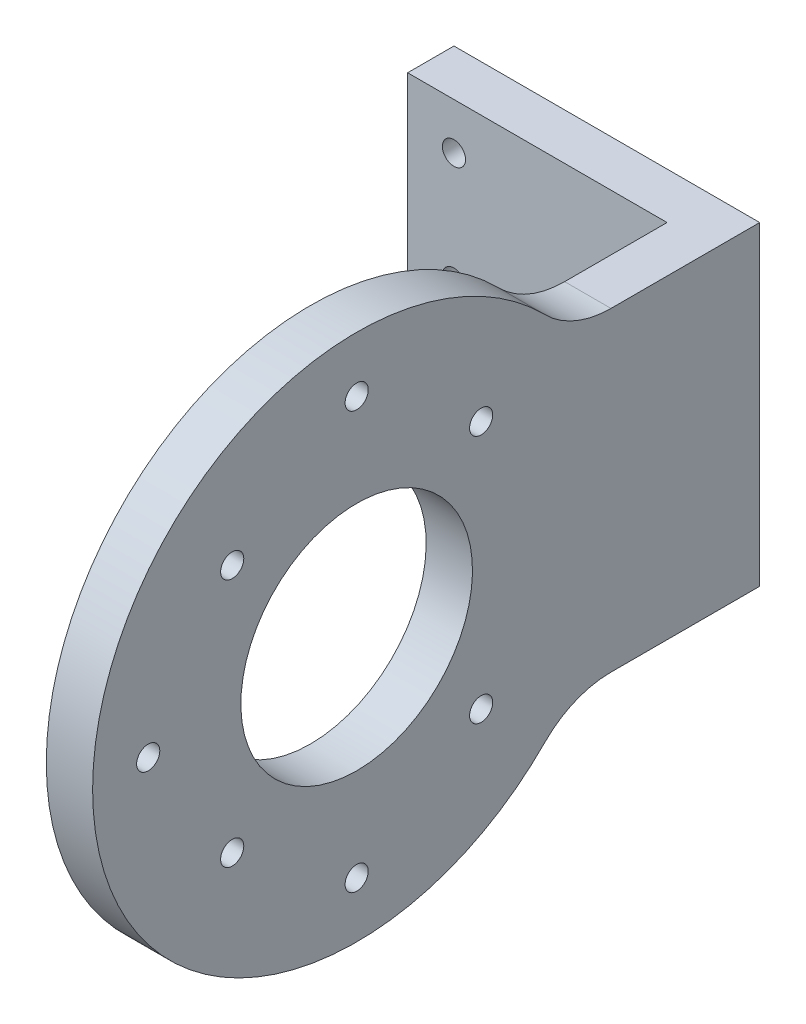
SolidWorks part; units mm, degrees
material "AISI 304"
ref_plane "前视基准面" through (0, 0, 0) normal (0, 0, 1) x (1, 0, 0)
ref_plane "上视基准面" through (0, 0, 0) normal (0, 1, 0) x (1, 0, 0)
ref_plane "右视基准面" through (0, 0, 0) normal (1, 0, 0) x (0, 0, -1)
other "Configuration Table"
sketch "草图1" plane through (0, 0, 0) normal (0, 0, 1) x (1, 0, 0)
  line L0 (23, 17) -> (28, 17)
  line L1 (-5, 17) -> (23, 17)
  line L3 (-5, -17) -> (23, -17)
  line L5 (-23, 17) -> (23, -17) construction
  line L6 (-23, -17) -> (23, 17) construction
  line L7 (28, 17) -> (28, -17)
  line L8 (28, -17) -> (23, -17)
  line L9 (-5, 17) -> (-5, -17)
  point P0 (0, 0)
  dimension "D1" = 46
  dimension "D2" = 34
  dimension "D3" = 5
extrude "凸台-拉伸1" add sketch "草图1" along normal blind 5
sketch "草图2" plane through (28, 0, 0) normal (1, 0, 0) x (0, 0, -1)
  line L0 (-5, 17) -> (-72, 17)
  line L1 (-72, 17) -> (-72, -17)
  line L2 (-72, -17) -> (-5, -17)
  line L3 (-5, -17) -> (-5, 17) construction
  line L4 (-5, 17) -> (-5, -17)
  dimension "D1" = 90
  dimension "D2" = 67
extrude "凸台-拉伸2" add sketch "草图2" against normal blind 5
sketch "草图4" plane through (23, 0, 0) normal (-1, 0, 0) x (0, 0, 1)
  line L0 (-7.5429, 0) -> (80.3262, 0) construction
  line L1 (43.5, 22.0479) -> (43.5, -26.7017) construction
  line L2 (72, 17) -> (72, -17) construction
  line L4 (15, 28.5) -> (72, 28.5)
  line L5 (15, 28.5) -> (15, -28.5)
  line L6 (15, -28.5) -> (72, -28.5)
  line L7 (72, 28.5) -> (72, -28.5)
  line L8 (15, 28.5) -> (72, -28.5) construction
  line L9 (15, -28.5) -> (72, 28.5) construction
  point P7 (43.5, 0)
  dimension "D1" = 28.5
  dimension "D2" = 57
  dimension "D3" = 57
extrude "凸台-拉伸3" add sketch "草图4" against normal blind 5
sketch "草图5" plane through (23, 0, 0) normal (-1, 0, 0) x (0, 0, 1)
  line L0 (72, 28.5) -> (72, -28.5) construction
  line L1 (15, -28.5) -> (72, -28.5) construction
  line L2 (15, 17) -> (20.6253, 17)
  line L3 (15, -17) -> (20.6253, -17)
  line L4 (15, -17) -> (15, -28.5) construction
  line L5 (15, 28.5) -> (15, 17) construction
  line L6 (72, 28.5) -> (15, 28.5) construction
  line L7 (72, 28.5) -> (72, -28.5)
  line L8 (15, -28.5) -> (72, -28.5)
  line L9 (15, -17) -> (15, -28.5)
  line L10 (15, 28.5) -> (15, 17)
  line L11 (72, 28.5) -> (15, 28.5)
  circle A0 centre (43.5, 0) radius 28.5
  line M3 (15, -17) -> (15, -28.5)
  line M4 (15, -28.5) -> (72, -28.5)
  line M5 (72, -28.5) -> (72, 28.5)
  line M6 (72, 28.5) -> (15, 28.5)
  line M7 (15, 28.5) -> (15, 17)
  dimension "D1" = 57
extrude "切除-拉伸1" cut sketch "草图5" against normal blind 5 contours A0 L11 L2 M7 | A0 L3 M3 M4 | A0 L8 M5 | A0 L7 M6
fillet "圆角1" radius 10 1 edges at (25.5, 17, 20.6253)
fillet "圆角2" radius 10 1 edges at (25.5, -17, 20.6253)
sketch "草图6" plane through (23, 0, 0) normal (-1, 0, 0) x (0, 0, 1)
  line L0 (-8.9217, 0) -> (88.0593, 0) construction
  line L1 (43.5, 28.5) -> (43.5, -28.5) construction
  line L2 (43.5, 0) -> (74.2733, 30.7733) construction
  arc A0 (23.1833, -19.987) -> (23.1833, 19.987) centre (43.5, 0) ccw construction
  circle A1 centre (56.935, 13.435) radius 1.25
  circle A2 centre (43.5, 0) radius 12.5
  dimension "D2" = 2.5
  dimension "D4" = 25
  dimension "D1" = 45
  dimension "D3" = 19
extrude "切除-拉伸2" cut sketch "草图6" against normal blind 5
pattern_circular "阵列(圆周)1" count 4 over 360 about axis through (0, 0, 43.5) along (1, 0, 0) of "切除-拉伸2"
sketch "草图7" plane through (0, 0, 5) normal (0, 0, 1) x (1, 0, 0)
  line L0 (-7.477, 0) -> (8.9509, 0) construction
  circle A0 centre (0, 0) radius 1.25
  circle A1 centre (0, 12) radius 1.25
  circle A2 centre (0, -12) radius 1.25
  dimension "D1" = 2.5
  dimension "D2" = 2.5
  dimension "D3" = 12
extrude "切除-拉伸3" cut sketch "草图7" against normal blind 5
sketch "草图8" plane through (28, 0, 0) normal (1, 0, 0) x (0, 0, -1)
  line L0 (-72, 0) -> (2.0956, 0) construction
  line L1 (-43.5, 28.5) -> (-43.5, -28.5) construction
  arc A0 (-23.1833, 19.987) -> (-23.1833, -19.987) centre (-43.5, 0) ccw construction
  circle A1 centre (-43.5, 22.5) radius 1.25
  dimension "D1" = 2.5
  dimension "D2" = 22.5
extrude "切除-拉伸5" cut sketch "草图8" against normal blind 10
pattern_circular "阵列(圆周)2" count 3 over 180 about axis through (0, 0, 43.5) along (1, 0, 0) of "切除-拉伸5"
